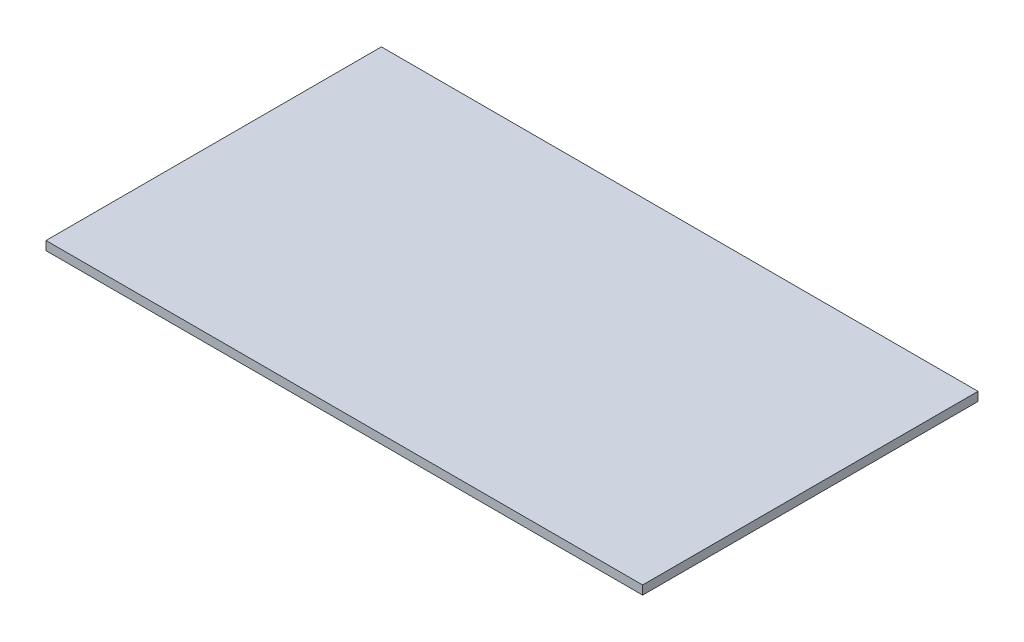
SolidWorks part; units mm, degrees
ref_plane "정면" through (0, 0, 0) normal (0, 0, 1) x (1, 0, 0)
ref_plane "윗면" through (0, 0, 0) normal (0, 1, 0) x (1, 0, 0)
ref_plane "우측면" through (0, 0, 0) normal (1, 0, 0) x (0, 0, -1)
sketch "스케치1" plane through (0, 0, 0) normal (0, 1, 0) x (1, 0, 0)
  line L1 (0, 0) -> (338, 0)
  line L2 (0, 0) -> (0, 190)
  line L3 (0, 190) -> (338, 190)
  line L4 (338, 0) -> (338, 190)
  dimension "D1" = 190
  dimension "D2" = 338
extrude "보스-돌출1" add sketch "스케치1" along normal blind 5
